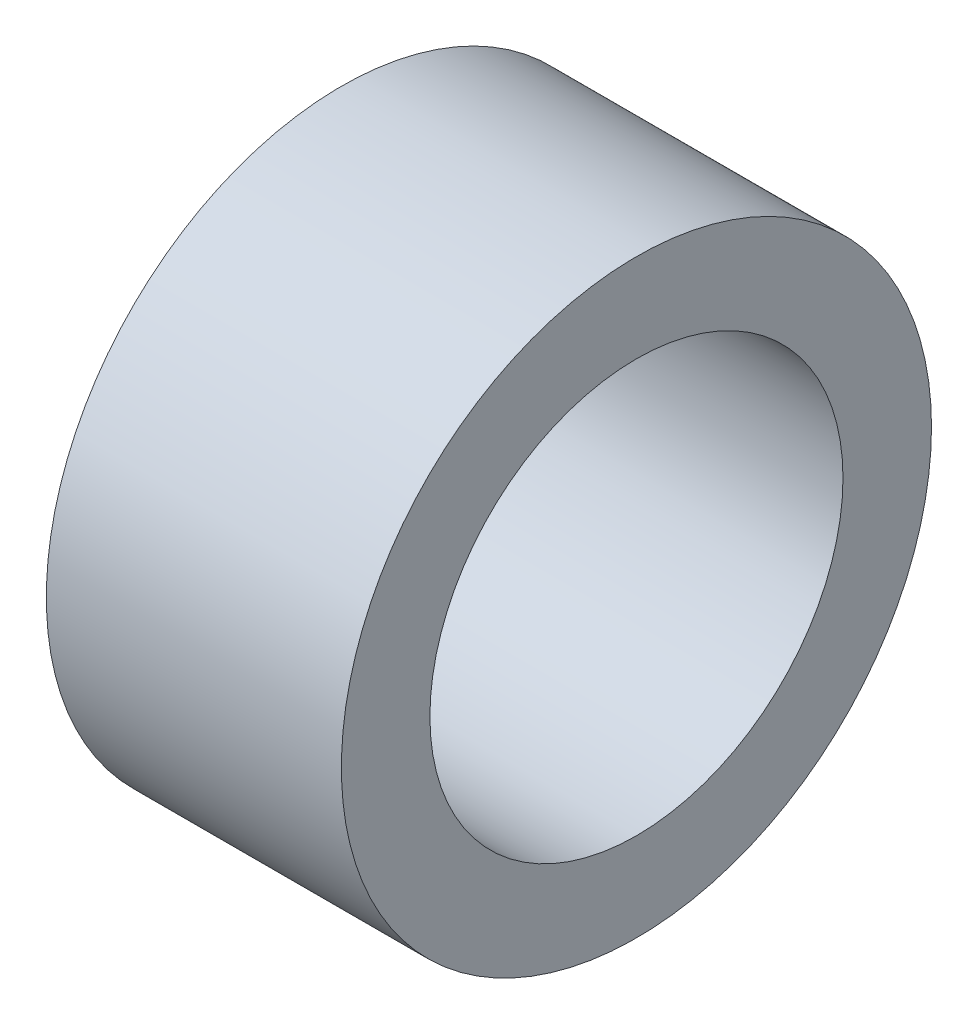
SolidWorks part; units mm, degrees
material "AISI 316 Stainless Steel Sheet (SS)"
ref_plane "Front Plane" through (0, 0, 0) normal (0, 0, 1) x (1, 0, 0)
ref_plane "Top Plane" through (0, 0, 0) normal (0, 1, 0) x (1, 0, 0)
ref_plane "Right Plane" through (0, 0, 0) normal (1, 0, 0) x (0, 0, -1)
sketch "Sketch1" plane through (0, 0, 0) normal (1, 0, 0) x (0, 0, -1)
  circle A0 centre (0, 0) radius 5
  circle A1 centre (0, 0) radius 3.5
  dimension "D1" = 10
  dimension "D2" = 1.5
extrude "Boss-Extrude1" add sketch "Sketch1" along normal blind 5
